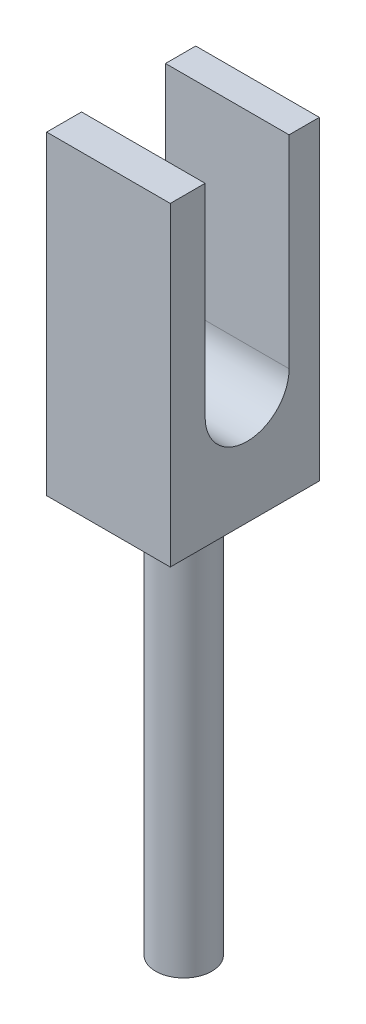
SolidWorks part; units mm, degrees
ref_plane "Front Plane" through (0, 0, 0) normal (0, 0, 1) x (1, 0, 0)
ref_plane "Top Plane" through (0, 0, 0) normal (0, 1, 0) x (1, 0, 0)
ref_plane "Right Plane" through (0, 0, 0) normal (1, 0, 0) x (0, 0, -1)
sketch "Sketch1" plane through (0, 0, 0) normal (1, 0, 0) x (0, 0, -1)
  line L1 (0, 0) -> (74.7573, 0)
  line L2 (0, 0) -> (0, 56.3408)
  line L3 (0, 56.3408) -> (74.7573, 56.3408)
  line L4 (74.7573, 0) -> (74.7573, 56.3408)
extrude "Boss-Extrude1" add sketch "Sketch1" along normal blind 61.976
sketch "Sketch2" plane through (61.976, 0, 0) normal (1, 0, 0) x (0, 0, -1)
  line L0 (74.7573, 56.3408) -> (0, 56.3408) construction
  circle A0 centre (38.5338, 56.3408) radius 21.0515
extrude "Cut-Extrude1" cut sketch "Sketch2" against normal blind 61.976
sketch "Sketch3" plane through (0, 56.3408, 0) normal (0, 1, 0) x (1, 0, 0)
  line L1 (61.976, 0) -> (0, 0)
  line L2 (61.976, 0) -> (61.976, 17.4822)
  line L3 (61.976, 17.4822) -> (0, 17.4822)
  line L4 (0, 0) -> (0, 17.4822)
extrude "Boss-Extrude2" add sketch "Sketch3" along normal blind 101.6
sketch "Sketch4" plane through (0, 0, 0) normal (0, -1, 0) x (1, 0, 0)
  circle A0 centre (30.6914, -38.046) radius 14.0914
extrude "Boss-Extrude3" add sketch "Sketch4" along normal blind 203.2
sketch "Sketch5" plane through (0, 56.3408, 0) normal (0, 1, 0) x (1, 0, 0)
  line L1 (0, 59.5853) -> (61.976, 59.5853)
  line L2 (0, 59.5853) -> (0, 74.7573)
  line L3 (0, 74.7573) -> (61.976, 74.7573)
  line L4 (61.976, 59.5853) -> (61.976, 74.7573)
extrude "Boss-Extrude4" add sketch "Sketch5" along normal blind 101.6
